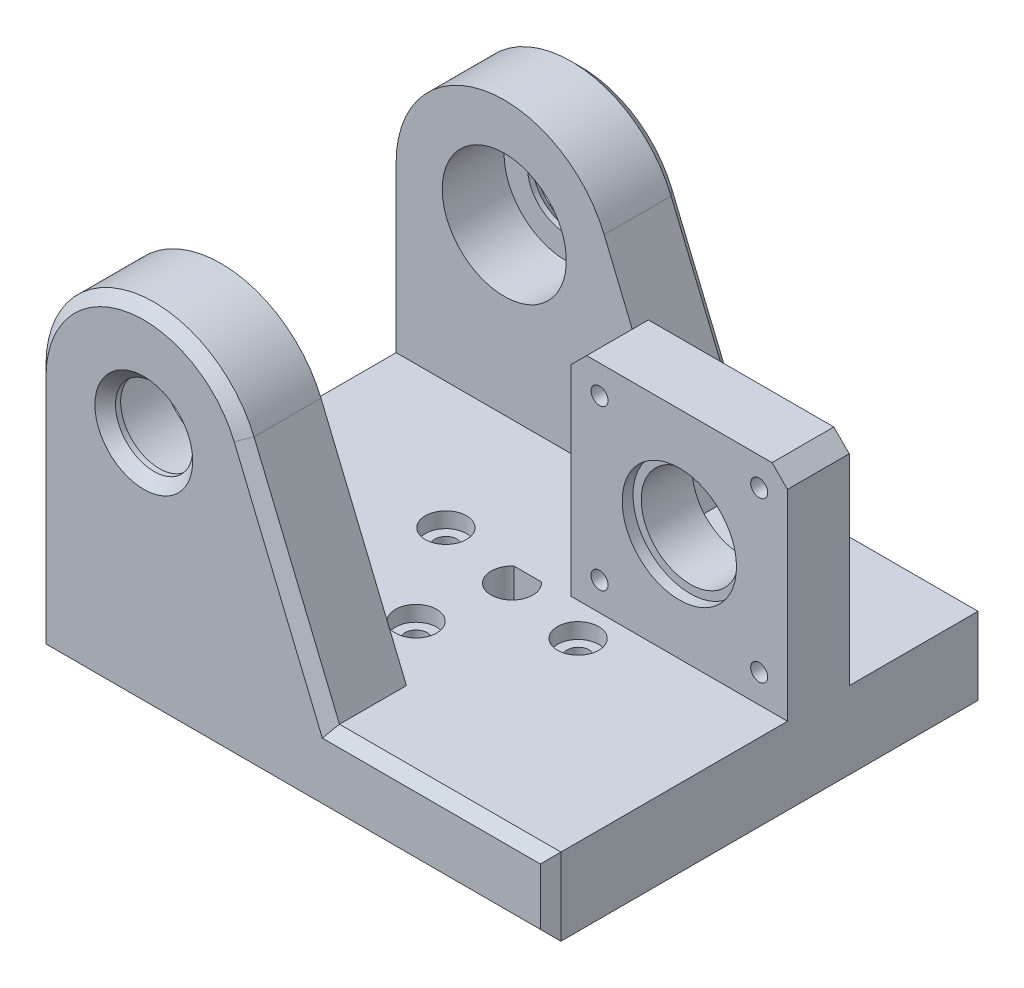
SolidWorks part; units mm, degrees
ref_plane "前视基准面" through (0, 0, 0) normal (0, 0, 1) x (1, 0, 0)
ref_plane "上视基准面" through (0, 0, 0) normal (0, 1, 0) x (1, 0, 0)
ref_plane "右视基准面" through (0, 0, 0) normal (1, 0, 0) x (0, 0, -1)
sketch "草图1" plane through (0, 0, 0) normal (0, 1, 0) x (1, 0, 0)
  line L1 (-50, -42.5) -> (50, -42.5)
  line L2 (-50, -42.5) -> (-50, 42.5)
  line L3 (-50, 42.5) -> (50, 42.5)
  line L4 (50, -42.5) -> (50, 42.5)
  line L5 (-50, -42.5) -> (50, 42.5) construction
  line L6 (-50, 42.5) -> (50, -42.5) construction
  point P0 (0, 0)
  dimension "D1" = 85
  dimension "D2" = 100
extrude "凸台-拉伸1" add sketch "草图1" along normal blind 15
sketch "草图2" plane through (0, 0, 42.5) normal (0, 0, 1) x (1, 0, 0)
  line L0 (-50, 15) -> (-50, 47)
  line L1 (-50, 15) -> (7, 15)
  line L2 (-9.6011, 55.0425) -> (7, 15)
  line L3 (-50, 15) -> (50, 15) construction
  line L4 (50, 15) -> (50, 0) construction
  arc A0 (-9.6011, 55.0425) -> (-50, 47) centre (-29, 47) ccw
  dimension "D2" = 21
  dimension "D1" = 43
  dimension "D3" = 32
extrude "凸台-拉伸2" add sketch "草图2" against normal blind 15
sketch "草图3" plane through (0, 0, -42.5) normal (0, 0, -1) x (-1, 0, 0)
  line L1 (-50, 15) -> (-8, 15)
  line L2 (-50, 15) -> (-50, 57)
  line L3 (-50, 57) -> (-8, 57)
  line L4 (-8, 15) -> (-8, 57)
  dimension "D1" = 42
  dimension "D2" = 42
extrude "凸台-拉伸3" add sketch "草图3" against normal blind 12 from offset 27 offset against normal yes
chamfer "倒角1" distance 3 angle 45 2 edges at (50, 57, -9.5) (8, 57, -9.5)
sketch "草图5" plane through (0, 0, -42.5) normal (0, 0, -1) x (-1, 0, 0)
  line L3 (-7, 15) -> (50, 15)
  line L4 (50, 15) -> (50, 47)
  line L5 (9.6011, 55.0425) -> (-7, 15)
  line L6 (-7, 15) -> (50, 15)
  line L7 (50, 15) -> (50, 47)
  line L8 (9.6011, 55.0425) -> (-7, 15)
  arc A1 (50, 47) -> (9.6011, 55.0425) centre (29, 47) ccw
  arc A2 (50, 47) -> (9.6011, 55.0425) centre (29, 47) ccw
  dimension "D1" = 0
extrude "凸台-拉伸4" add sketch "草图5" against normal blind 15
sketch "草图6" plane through (0, 0, 0) normal (0, -1, 0) x (1, 0, 0)
  circle A0 centre (0, 0) radius 27.5
  dimension "D1" = 55
extrude "凸台-拉伸5" add sketch "草图6" along normal blind 23
sketch "草图7" plane through (0, -23, 0) normal (0, -1, 0) x (1, 0, 0)
  circle A0 centre (0, 0) radius 24
  dimension "D1" = 48
extrude "凸台-拉伸6" add sketch "草图7" along normal blind 7
sketch "草图8" plane through (0, -30, 0) normal (0, -1, 0) x (1, 0, 0)
  circle A0 centre (0, 0) radius 12.5
  dimension "D1" = 25
extrude "凸台-拉伸7" add sketch "草图8" along normal blind 7
sketch "草图9" plane through (0, 0, -15.5) normal (0, 0, -1) x (-1, 0, 0)
  line L0 (-9.5, 55.5) -> (-50, 15) construction
  line L1 (-8, 54) -> (-11, 57) construction
  line L2 (-29, 57) -> (-29, 21.7393) construction
  line L3 (-11, 57) -> (-47, 57) construction
  circle A0 centre (-29, 36) radius 9.5
  dimension "D1" = 19
extrude "切除-拉伸1" cut sketch "草图9" against normal blind 15
sketch "草图10" plane through (0, 0, 0) normal (0, -1, 0) x (1, 0, 0)
  circle A0 centre (0, 0) radius 39
  circle A1 centre (0, 0) radius 27.5
  dimension "D1" = 78
  dimension "D2" = 55
sketch "草图11" plane through (0, -30, 0) normal (0, -1, 0) x (1, 0, 0)
  circle A1 centre (0, 0) radius 27.5
  dimension "D1" = 55
extrude "凸台-拉伸9" add sketch "草图11" along normal blind 2
sketch "草图12" plane through (0, 0, 0) normal (0, 0, 1) x (1, 0, 0)
  circle A0 centre (-29, 47) radius 12.05
  dimension "D1" = 24.1
extrude "切除-拉伸2" cut sketch "草图12" against normal blind 39.5 and the other way blind 39.5
sketch "草图13" plane through (0, 0, 42.5) normal (0, 0, 1) x (1, 0, 0)
  circle A0 centre (-29, 47) radius 7.5
  dimension "D1" = 15
extrude "切除-拉伸3" cut sketch "草图13" against normal through all
chamfer "倒角2" distance 2 angle 45 7 edges at (-50, 23.5, 42.5) (-33.1002, 67.5958, 42.5) (-1.3005, 35.0213, 42.5) (28.5, 15, 42.5) (50, 7.5, 42.5) (0, 0, 42.5) (-21.5, 47, 42.5)
chamfer "倒角3" distance 2 angle 45 7 edges at (50, 7.5, -42.5) (28.5, 15, -42.5) (-1.3005, 35.0213, -42.5) (-33.1002, 67.5958, -42.5) (-50, 23.5, -42.5) (0, 0, -42.5) (-21.5, 47, -42.5)
extrude "切除-拉伸4" cut sketch "草图10" against normal blind 3.5
ref_plane "基准面1" through (0, 47, 0) normal (0, 1, 0) x (1, 0, 0)
sketch "草图14" plane through (0, 47, 0) normal (0, 1, 0) x (1, 0, 0)
  point P0 (0, 0)
sketch "草图15" plane through (0, 0, -3.5) normal (0, 0, 1) x (1, 0, 0)
  circle A0 centre (44.5, 51.5) radius 1.65
  circle A1 centre (13.5, 51.5) radius 1.65
  circle A2 centre (13.5, 20.5) radius 1.65
  circle A3 centre (44.5, 20.5) radius 1.65
  dimension "D1" = 3.3
extrude "切除-拉伸5" cut sketch "草图15" against normal through all
sketch "草图16" plane through (0, 0, -42.5) normal (0, 0, -1) x (-1, 0, 0)
  line L1 (-50, 0) -> (55.4415, 0)
  line L2 (-50, 0) -> (-50, -43.6775)
  line L3 (-50, -43.6775) -> (55.4415, -43.6775)
  line L4 (55.4415, 0) -> (55.4415, -43.6775)
extrude "切除-拉伸6" cut sketch "草图16" against normal through all
sketch "草图17" plane through (0, 0, 0) normal (0, 1, 0) x (1, 0, 0)
  circle A0 centre (0, 0) radius 16 construction
  circle A1 centre (-2.8989, -15.7352) radius 2.15
  circle A2 centre (-15.7352, 2.8989) radius 2.15
  circle A3 centre (2.8989, 15.7352) radius 2.15
  circle A4 centre (15.7352, -2.8989) radius 2.15
  point P14 (0, 0)
  dimension "D1" = 32
  dimension "D2" = 4.3
  dimension "D3" = 4
extrude "切除-拉伸7" cut sketch "草图17" along normal through all both and the other way through all
sketch "草图18" plane through (0, 15, 0) normal (0, 1, 0) x (1, 0, 0)
  circle A0 centre (2.8989, 15.7352) radius 4
  circle A1 centre (15.7352, -2.8989) radius 4
  circle A2 centre (-2.8989, -15.7352) radius 4
  circle A3 centre (-15.7352, 2.8989) radius 4
  dimension "D1" = 8
extrude "切除-拉伸8" cut sketch "草图18" against normal blind 3
sketch "草图19" plane through (0, 15, 0) normal (0, 1, 0) x (1, 0, 0)
  line L0 (0, 0) -> (0, 4.05) construction
  line L1 (-2.6646, 3.05) -> (2.6646, 3.05)
  arc A0 (-2.6646, 3.05) -> (2.6646, 3.05) centre (0, 0) ccw
  dimension "D1" = 8.1
  dimension "D2" = 3.05
extrude "切除-拉伸9" cut sketch "草图19" against normal through all
sketch "草图20" plane through (0, 0, -3.5) normal (0, 0, 1) x (1, 0, 0)
  circle A0 centre (29, 36) radius 11.1
  dimension "D1" = 22.2
extrude "切除-拉伸10" cut sketch "草图20" against normal blind 2.1
sketch "草图21" plane through (50, 0, 0) normal (1, 0, 0) x (0, 0, -1)
  line L0 (15.5, 25) -> (15.5, 15)
  line L1 (15.5, 54) -> (15.5, 15) construction
  line L2 (15.5, 15) -> (25.5, 15)
  line L3 (15.5, 15) -> (40.5, 15) construction
  line L4 (25.5, 15) -> (15.5, 25)
  dimension "D1" = 10
  dimension "D2" = 10
extrude "凸台-拉伸10" add sketch "草图21" against normal blind 18 from offset 12 offset against normal yes
